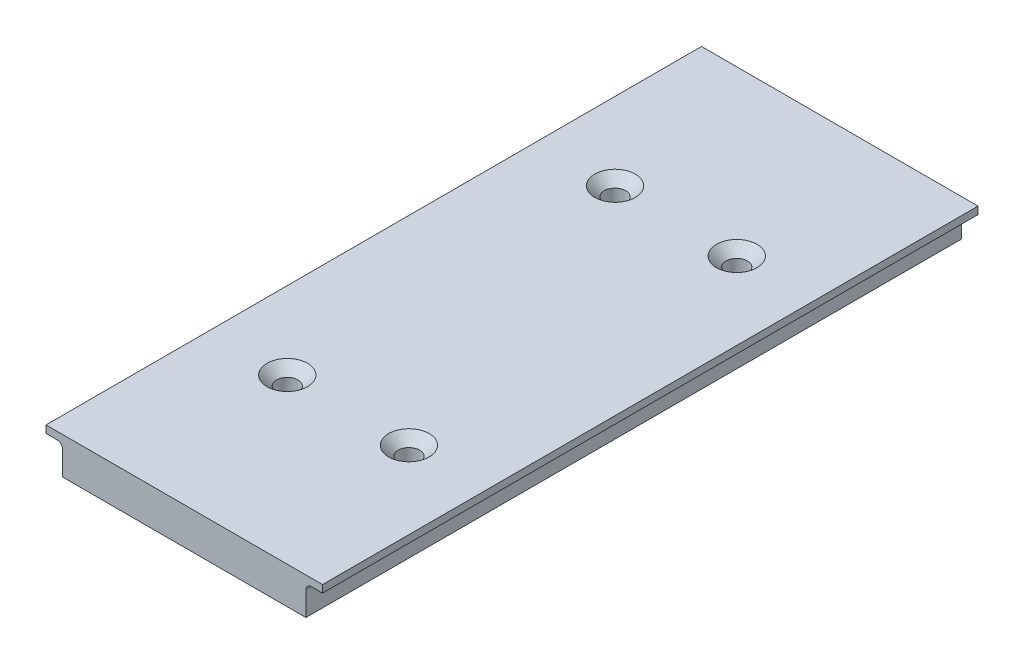
SolidWorks part; units mm, degrees
material "ABS"
ref_plane "Front Plane" through (0, 0, 0) normal (0, 0, 1) x (1, 0, 0)
ref_plane "Top Plane" through (0, 0, 0) normal (0, 1, 0) x (1, 0, 0)
ref_plane "Right Plane" through (0, 0, 0) normal (1, 0, 0) x (0, 0, -1)
sketch "Sketch1" plane through (0, 0, 0) normal (0, 0, 1) x (1, 0, 0)
  line L0 (-16.5, 3.25) -> (-16.5, 0)
  line L1 (-16.5, 0) -> (16.5, 0)
  line L2 (-18.75, 4) -> (-18.75, 5)
  line L3 (-18.75, 5) -> (18.75, 5)
  line L4 (0, 0) -> (0, 5) construction
  line L5 (-18.75, 4) -> (-17.25, 4)
  line L6 (18.75, 4) -> (17.25, 4)
  line L7 (18.75, 4) -> (18.75, 5)
  line L8 (16.5, 3.25) -> (16.5, 0)
  arc A0 (-17.25, 4) -> (-16.5, 3.25) centre (-17.25, 3.25) cw
  arc A1 (17.25, 4) -> (16.5, 3.25) centre (17.25, 3.25) ccw
  dimension "D1" = 18.75
  dimension "D2" = 5
  dimension "D3" = 2.25
  dimension "D4" = 3.25
  dimension "D5" = 1
  dimension "D6" = 1.5
extrude "Boss-Extrude1" add sketch "Sketch1" along normal blind 88.9
sketch "Sketch2" plane through (0, 5, 0) normal (0, 1, 0) x (1, 0, 0)
  line L0 (18.75, -88.9) -> (-18.75, -88.9) construction
  line L1 (16.5, -88.9) -> (-16.5, -88.9)
  line L2 (16.5, -88.9) -> (16.5, 0)
  line L3 (16.5, 0) -> (-16.5, 0)
  line L4 (-16.5, -88.9) -> (-16.5, 0)
  line L5 (0, 0) -> (0, -88.9) construction
  line L6 (16.5, -44.45) -> (-16.5, -44.45) construction
  line L7 (18.75, 0) -> (-18.75, 0) construction
  line L8 (-18.75, -88.9) -> (-18.75, 0) construction
  line L9 (18.75, -88.9) -> (18.75, 0) construction
  line L10 (16.5, -88.9) -> (-16.5, 0) construction
  line L11 (-16.5, -88.9) -> (16.5, 0) construction
  line L13 (8.2506, -66.6767) -> (-8.2506, -66.6767)
  line L14 (8.2506, -66.6767) -> (8.2506, -22.2233)
  line L15 (8.2506, -22.2233) -> (-8.2506, -22.2233)
  line L16 (-8.2506, -66.6767) -> (-8.2506, -22.2233)
  line L17 (0, -22.2233) -> (0, -66.6767) construction
  line L18 (8.2506, -44.45) -> (-8.2506, -44.45) construction
  point P12 (8.2506, -66.6767)
  point P13 (0, -44.45)
  point P14 (-8.2506, -22.2233)
  point P15 (-16.5, 0)
  point P16 (43.8256, -62.2482)
  point P21 (8.2506, -22.2233)
  point P22 (-8.2506, -66.6767)
  point P176 (0, -44.45)
  point P294 (0, -44.45)
  dimension "D1" = 2.25
  dimension "D2" = 2.25
  dimension "D3" = 23.705
  dimension "D4" = 23.705
hole_wizard "CSK for M2.5 Flat Head Machine Screw1" positions "Sketch5" profile "Sketch4" countersink size "M2.5" standard "ANSI Metric" end condition through all
sketch "Sketch5" plane through (0, 5, 0) normal (0, 1, 0) x (1, 0, 0)
  point P0 (8.2506, -22.2233)
  point P2 (-8.2506, -22.2233)
  point P4 (-8.2506, -66.6767)
  point P6 (8.2506, -66.6767)
sketch "Sketch4" plane through (8.2506, 5, 22.2233) normal (1, 0, 0) x (0, 0, 1)
  line L0 (0, 0) -> (0, 5)
  line L1 (0, 5) -> (1.45, 5)
  line L2 (1.45, 5) -> (1.45, 1.3)
  line L3 (1.45, 1.3) -> (2.75, 0)
  line L5 (2.75, 0) -> (0, 0)
  line L6 (-1.45, 1.3) -> (-2.75, 0) construction
  line L11 (0, -6.35) -> (0, 107.95) construction
  dimension "Thru Hole Dia." = 2.9
  dimension "Thru Hole Depth" = 5
  dimension "Near C'Sink Dia." = 5.5
  dimension "Near C'Sink Angle" = 90
